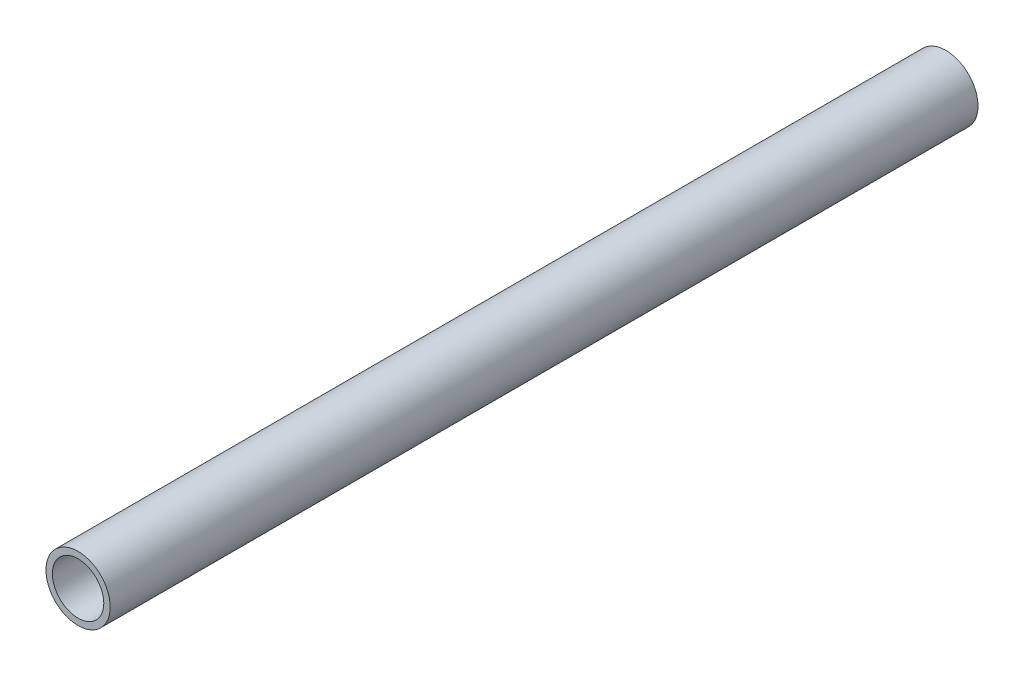
SolidWorks part; units mm, degrees
ref_plane "Front Plane" through (0, 0, 0) normal (0, 0, 1) x (1, 0, 0)
ref_plane "Top Plane" through (0, 0, 0) normal (0, 1, 0) x (1, 0, 0)
ref_plane "Right Plane" through (0, 0, 0) normal (1, 0, 0) x (0, 0, -1)
sketch "Sketch1" plane through (0, 0, 0) normal (0, 0, 1) x (1, 0, 0)
  circle A0 centre (0, 0) radius 10
  dimension "D1" = 20
extrude "Extrude-Thin1" add sketch "Sketch1" along normal blind 270 thin thin type one direction reverse wall 2
sketch "Sketch2" plane through (0, 0, 0) normal (0, 0, -1) x (-1, 0, 0)
  line L0 (0, 12.5419) -> (0, -12.9874) construction
  line L1 (0, -12.9874) -> (-13.8554, -0.2227) construction
  line L2 (-13.8554, -0.2227) -> (17.9872, -0.2227) construction
